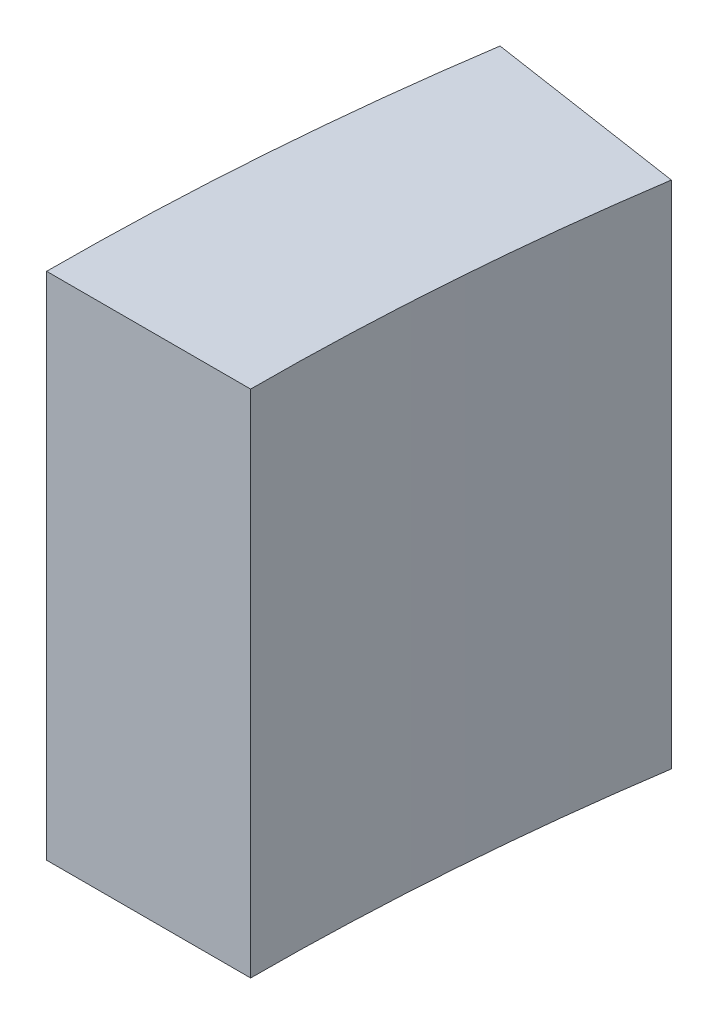
SolidWorks part; units mm, degrees
ref_plane "Front Plane" through (0, 0, 0) normal (0, 0, 1) x (1, 0, 0)
ref_plane "Top Plane" through (0, 0, 0) normal (0, 1, 0) x (1, 0, 0)
ref_plane "Right Plane" through (0, 0, 0) normal (1, 0, 0) x (0, 0, -1)
sketch "Sketch1" plane through (0, 0, 0) normal (0, 1, 0) x (1, 0, 0)
  circle A0 centre (0, 0) radius 55.5
  circle A1 centre (0, 0) radius 51.5
  dimension "D1" = 111
  dimension "D2" = 4
extrude "Boss-Extrude1" add sketch "Sketch1" along normal blind 10
sketch "Sketch2" plane through (0, 10, 0) normal (0, 1, 0) x (1, 0, 0)
  line L0 (0, 0) -> (-65.56, 0)
  line L1 (0, 0) -> (-64.828, 9.7696)
  arc A0 (-65.56, 0) -> (-64.828, 9.7696) centre (0, 0) ccw
  dimension "D1" = 8.57
extrude "Cut-Extrude1" cut sketch "Sketch2" against normal through all
